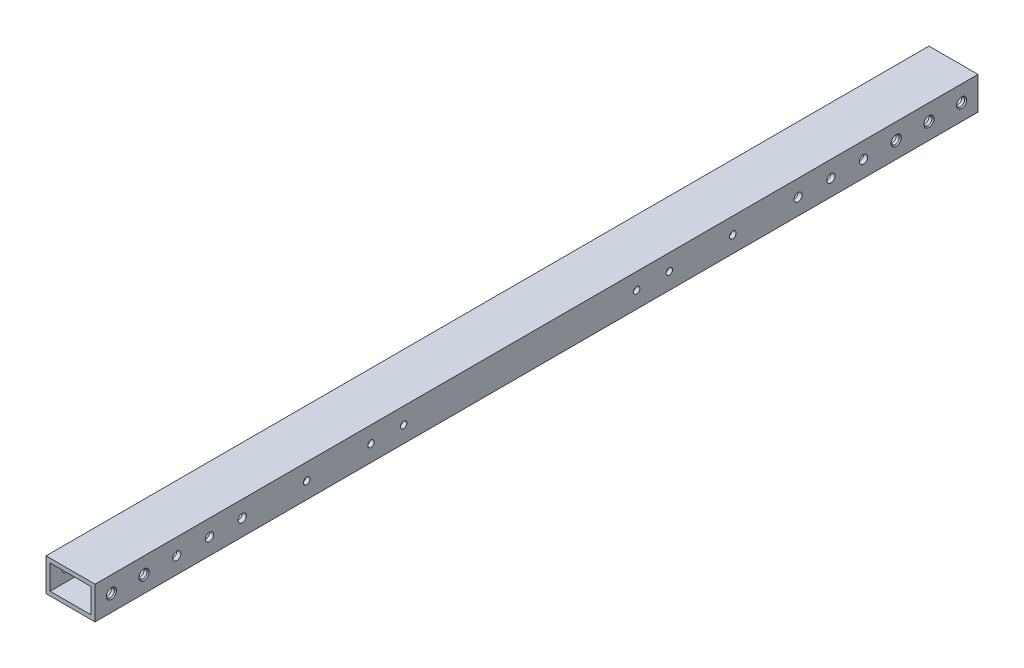
SolidWorks part; units mm, degrees
ref_plane "Front Plane" through (0, 0, 0) normal (0, 0, 1) x (1, 0, 0)
ref_plane "Top Plane" through (0, 0, 0) normal (0, 1, 0) x (1, 0, 0)
ref_plane "Right Plane" through (0, 0, 0) normal (1, 0, 0) x (0, 0, -1)
sketch "Sketch1" plane through (0, 0, 0) normal (0, 0, 1) x (1, 0, 0)
  line L0 (-15.875, 9.525) -> (15.875, 9.525)
  line L2 (-19.05, 12.7) -> (19.05, 12.7)
  line L3 (-19.05, 12.7) -> (-19.05, -12.7)
  line L4 (-19.05, -12.7) -> (19.05, -12.7)
  line L5 (19.05, 12.7) -> (19.05, -12.7)
  line L10 (15.875, 9.525) -> (15.875, -9.525)
  line L11 (-15.875, -9.525) -> (15.875, -9.525)
  line L12 (-15.875, 9.525) -> (-15.875, -9.525)
  point P12 (0, 12.7)
  point P14 (19.05, 0)
  dimension "Wall Thickness" = 3.175
  dimension "Outside Width" = 38.1
  dimension "Outside Height" = 25.4
  dimension "Inside Height" = 19.05
  dimension "Inside Width" = 31.75
sketch "Sketch2" plane through (0, 0, 0) normal (1, 0, 0) x (0, 0, -1)
  line L0 (342.9, 0) -> (-342.9, 0)
  point P4 (0, 0)
  point P7 (-342.9, 0)
  point P10 (342.9, 0)
  dimension "Length" = 685.8
sketch "Sketch3" plane through (0, 0, 0) normal (0, 0, 1) x (1, 0, 0)
  line L21 (19.05, 12.7) -> (-19.05, 12.7)
  line L22 (19.05, -12.7) -> (19.05, 12.7)
  line L23 (-19.05, -12.7) -> (19.05, -12.7)
  line L24 (-19.05, 12.7) -> (-19.05, -12.7)
  line L25 (19.05, 12.7) -> (-19.05, 12.7)
  line L26 (19.05, -12.7) -> (19.05, 12.7)
  line L27 (-19.05, -12.7) -> (19.05, -12.7)
  line L28 (-19.05, 12.7) -> (-19.05, -12.7)
  line L29 (15.875, 9.525) -> (-15.875, 9.525)
  line L30 (15.875, -9.525) -> (15.875, 9.525)
  line L31 (-15.875, -9.525) -> (15.875, -9.525)
  line L32 (-15.875, 9.525) -> (-15.875, -9.525)
  line L33 (15.875, 9.525) -> (-15.875, 9.525)
  line L34 (15.875, -9.525) -> (15.875, 9.525)
  line L35 (-15.875, -9.525) -> (15.875, -9.525)
  line L36 (-15.875, 9.525) -> (-15.875, -9.525)
  dimension "D1" = 0
  dimension "D2" = 0
extrude "Boss-Extrude1" add sketch "Sketch3" along normal up to vertex (342.9 mm away) and the other way up to vertex (342.9 mm away) up to point (0, 0, 342.9) other way up to point (0, 0, -342.9)
sketch "Drawing Reference" plane through (0, 0, 0) normal (1, 0, 0) x (0, 0, -1)
  line L0 (-342.9, 0) -> (342.9, 0) construction
  line L1 (0, -12.7) -> (0, 12.7) construction
  line L2 (-342.9, -12.7) -> (342.9, -12.7) construction
  line L5 (-342.9, 12.7) -> (342.9, 12.7) construction
  point P7 (-315.468, 0)
  point P8 (315.468, 0)
  dimension "D1" = 27.432
sketch "Sketch4" plane through (-19.05, 0, 0) normal (-1, 0, 0) x (0, 0, 1)
  line L0 (-342.9, 0) -> (-330.2, 0)
  line L1 (-342.9, 12.7) -> (-342.9, -12.7) construction
  line L2 (-330.2, 0) -> (-304.8, 0)
  line L3 (-304.8, 0) -> (-279.4, 0)
  line L4 (-279.4, 0) -> (-254, 0)
  line L5 (-254, 0) -> (-228.6, 0)
  line L6 (-228.6, 0) -> (-203.2, 0)
  line L7 (342.9, 0) -> (330.2, 0)
  line L8 (342.9, 12.7) -> (342.9, -12.7) construction
  line L9 (330.2, 0) -> (304.8, 0)
  line L10 (304.8, 0) -> (279.4, 0)
  line L11 (279.4, 0) -> (254, 0)
  line L12 (254, 0) -> (228.6, 0)
hole_wizard "1/4 (0.25) Diameter Hole2" positions "Sketch7" profile "Sketch8" hole size "1/4" standard "ANSI Inch" end condition through all
sketch "Sketch7" plane through (-19.05, 0, 0) normal (-1, 0, 0) x (0, 0, 1)
  point P0 (-330.2, 0)
  point P3 (-304.8, 0)
  point P7 (330.2, 0)
  point P11 (-279.4, 0)
  point P14 (304.8, 0)
sketch "Sketch8" plane through (-19.05, 0, -330.2) normal (0, 1, 0) x (0, 0, 1)
  line L0 (0, 0) -> (0, 38.1)
  line L1 (0, 38.1) -> (3.9624, 38.1)
  line L2 (3.175, 37.1942) -> (3.175, 0)
  line L5 (3.175, 0) -> (0, 0)
  line L7 (3.9624, 38.1) -> (3.175, 37.1942)
  line L8 (-3.9624, 38.1) -> (-3.175, 37.1942) construction
  line L11 (0, -6.35) -> (0, 107.95) construction
  dimension "Thru Hole Dia." = 6.35
  dimension "Thru Hole Depth" = 38.1
  dimension "Far C'Sink Dia." = 7.9248
  dimension "Far C'Sink Angle" = 82
hole_wizard "1/4 (0.25) Diameter Hole3" positions "Sketch9" profile "Sketch10" hole size "1/4" standard "ANSI Inch" end condition through all
sketch "Sketch9" plane through (19.05, 0, 0) normal (1, 0, 0) x (0, 0, -1)
  point P0 (-279.4, 0)
  point P3 (-254, 0)
  point P6 (-228.6, 0)
  point P9 (254, 0)
  point P12 (228.6, 0)
  point P15 (203.2, 0)
sketch "Sketch10" plane through (19.05, 0, 279.4) normal (0, 1, 0) x (0, 0, -1)
  line L0 (0, 0) -> (0, 38.1)
  line L1 (0, 38.1) -> (3.175, 38.1)
  line L2 (3.175, 38.1) -> (3.175, 0)
  line L5 (3.175, 0) -> (0, 0)
  line L11 (0, -6.35) -> (0, 107.95) construction
  dimension "Thru Hole Dia." = 6.35
  dimension "Thru Hole Depth" = 38.1
hole_wizard "13/64 (0.20313) Diameter Hole1" positions "Sketch11" profile "Sketch12" hole size "13/64" standard "ANSI Inch" end condition through all
sketch "Sketch11" plane through (19.05, 0, 0) normal (1, 0, 0) x (0, 0, -1)
  point P0 (152.4, 0)
  point P3 (-178.5118, 0)
sketch "Sketch12" plane through (19.05, 0, -152.4) normal (0, 1, 0) x (0, 0, -1)
  line L0 (0, 0) -> (0, 38.1)
  line L1 (0, 38.1) -> (2.5798, 38.1)
  line L2 (2.5798, 38.1) -> (2.5798, 0)
  line L5 (2.5798, 0) -> (0, 0)
  line L11 (0, -6.35) -> (0, 107.95) construction
  dimension "Thru Hole Dia." = 5.1595
  dimension "Thru Hole Depth" = 38.1
sketch "Sketch13" plane through (19.05, 0, 0) normal (1, 0, 0) x (0, 0, -1)
  line L0 (-103.1875, 0) -> (-128.5875, 0)
  line L1 (77.7875, 0) -> (103.1875, 0)
hole_wizard "#10 Clearance Hole1" positions "Sketch14" profile "Sketch15" hole size "#10" standard "ANSI Inch" end condition through all
sketch "Sketch14" plane through (19.05, 0, 0) normal (1, 0, 0) x (0, 0, -1)
  point P0 (-128.5875, 0)
  point P3 (-103.1875, 0)
  point P7 (77.7875, 0)
  point P10 (103.1875, 0)
sketch "Sketch15" plane through (19.05, 0, 128.5875) normal (0, 1, 0) x (0, 0, -1)
  line L0 (0, 0) -> (0, 38.1)
  line L1 (0, 38.1) -> (2.4892, 38.1)
  line L2 (2.4892, 38.1) -> (2.4892, 0)
  line L5 (2.4892, 0) -> (0, 0)
  line L11 (0, -6.35) -> (0, 107.95) construction
  dimension "Thru Hole Dia." = 4.9784
  dimension "Thru Hole Depth" = 38.1
equation "\"D1@Drawing Reference\"=\"Outside Width@Sketch1\" * 0.72"
